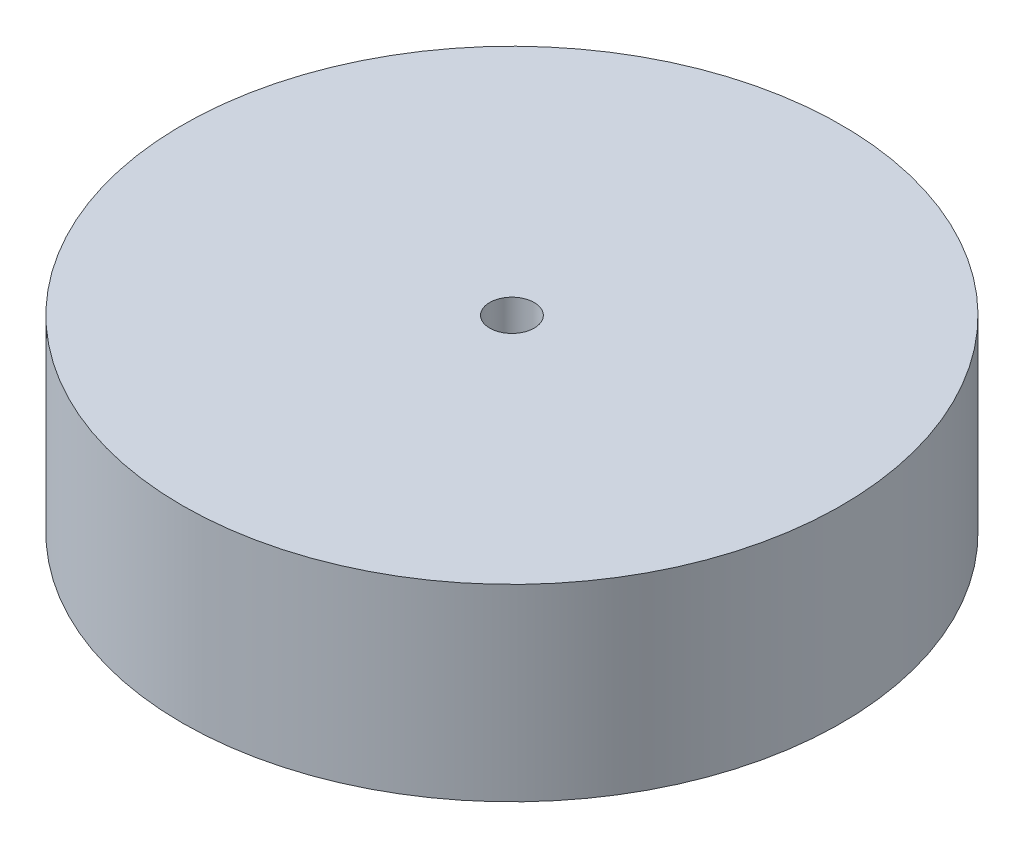
SolidWorks part; units mm, degrees
material "NEOPRENE"
ref_plane "Front Plane" through (0, 0, 0) normal (0, 0, 1) x (1, 0, 0)
ref_plane "Top Plane" through (0, 0, 0) normal (0, 1, 0) x (1, 0, 0)
ref_plane "Right Plane" through (0, 0, 0) normal (1, 0, 0) x (0, 0, -1)
sketch "Sketch1" plane through (0, 0, 0) normal (0, 1, 0) x (1, 0, 0)
  circle A0 centre (0, 0) radius 22.225
  circle A1 centre (0, 0) radius 1.5
  dimension "D1" = 44.45
  dimension "D2" = 3
extrude "Boss-Extrude1" add sketch "Sketch1" along normal blind 12.7
